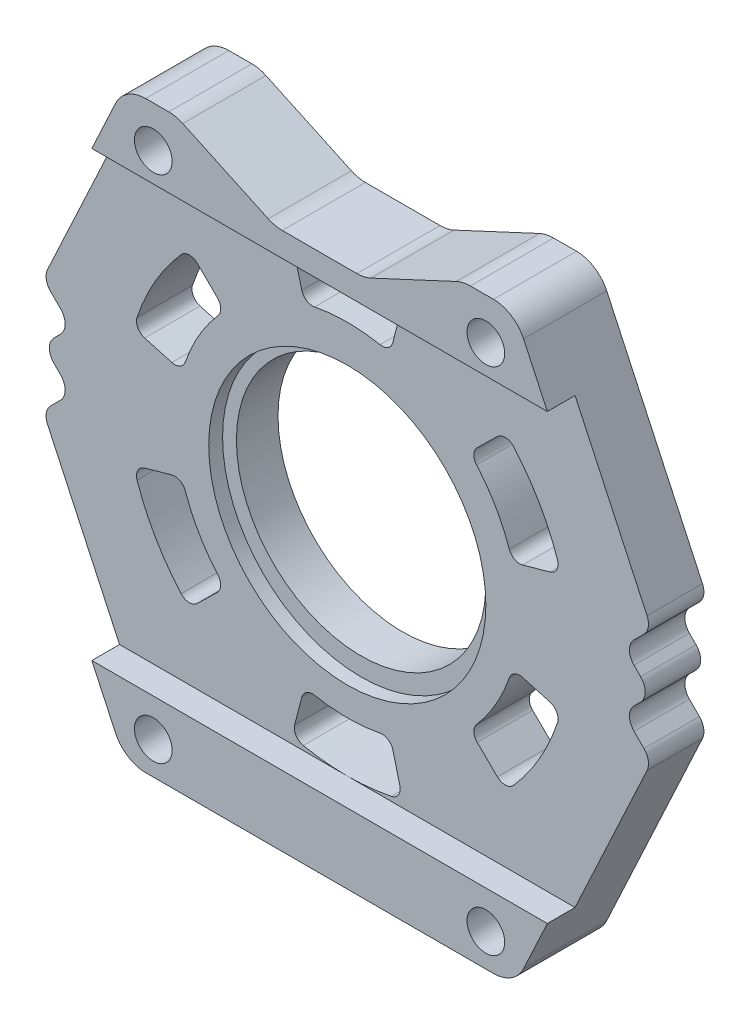
SolidWorks part; units mm, degrees
ref_plane "Front Plane" through (0, 0, 0) normal (0, 0, 1) x (1, 0, 0)
ref_plane "Top Plane" through (0, 0, 0) normal (0, 1, 0) x (1, 0, 0)
ref_plane "Right Plane" through (0, 0, 0) normal (1, 0, 0) x (0, 0, -1)
sketch "Sketch1" plane through (0, 0, 0) normal (0, 0, 1) x (1, 0, 0)
  line L1 (-34.8678, -33.4454) -> (34.8678, -33.4455)
  line L2 (-34.8678, -33.4454) -> (-34.8678, 33.4455)
  line L3 (-34.8678, 33.4455) -> (34.8678, 33.4455)
  line L4 (34.8678, -33.4455) -> (34.8678, 33.4455)
  line L5 (-34.8678, -33.4454) -> (34.8678, 33.4455) construction
  line L6 (-34.8678, 33.4455) -> (34.8678, -33.4455) construction
  circle A0 centre (0, 0) radius 14.2875
  point P0 (0, 0)
  dimension "D3" = 28.575
  dimension "D1" = 66.8909
  dimension "D2" = 69.7357
extrude "Boss-Extrude1" add sketch "Sketch1" along normal blind 9.525
sketch "Sketch2" plane through (0, 0, 9.525) normal (0, 0, 1) x (1, 0, 0)
  line L1 (-44.9984, -25.4) -> (44.9984, -25.4)
  line L2 (-44.9984, -25.4) -> (-44.9984, 25.4)
  line L3 (-44.9984, 25.4) -> (44.9984, 25.4)
  line L4 (44.9984, -25.4) -> (44.9984, 25.4)
  line L5 (-44.9984, -25.4) -> (44.9984, 25.4) construction
  line L6 (-44.9984, 25.4) -> (44.9984, -25.4) construction
  point P0 (0, 0)
  dimension "D1" = 50.8
extrude "Cut-Extrude1" cut sketch "Sketch2" against normal blind 3.175
sketch "Sketch3" plane through (0, 0, 6.35) normal (0, 0, 1) x (1, 0, 0)
  line L0 (-34.8678, -33.4454) -> (34.8678, -33.4455) construction
  line L1 (-34.8678, -33.4454) -> (34.8678, -33.4455) construction
  line L2 (0, -33.4455) -> (0, -16.3766) construction
  circle A0 centre (0, -0.5016) radius 15.875
  dimension "D1" = 31.75
  dimension "D2" = 17.0688
extrude "Cut-Extrude2" cut sketch "Sketch3" against normal blind 1.5875
sketch "Sketch4" plane through (0, 0, 0) normal (0, 0, -1) x (-1, 0, 0)
  line L0 (0, 0) -> (0, 33.4455) construction
  line L1 (-34.8678, 33.4455) -> (34.8678, 33.4455) construction
  line L2 (5.1189, 28.1763) -> (-5.1189, 28.1763)
  line L3 (-5.1189, 28.1763) -> (-16.436, 33.4455)
  line L4 (-16.436, 33.4455) -> (-22.3463, 33.4455)
  line L5 (-22.3463, 33.4455) -> (-34.8678, 6.5517)
  line L6 (-34.8678, -33.4455) -> (-34.8678, 33.4455) construction
  line L7 (-34.8678, 6.5517) -> (-31.592, 3.2758)
  line L8 (-31.592, 3.2758) -> (-34.8678, 0)
  line L9 (0, 0) -> (-34.8678, 0) construction
  line L11 (-48.1322, -47.2485) -> (-48.1322, 47.2485)
  line L13 (48.1322, 47.2485) -> (-48.1322, 47.2485)
  line L14 (48.1322, 0) -> (48.1322, 47.2485)
  line L16 (31.592, 3.2758) -> (34.8678, 0)
  line L17 (34.8678, 6.5517) -> (31.592, 3.2758)
  line L18 (22.3463, 33.4455) -> (34.8678, 6.5517)
  line L19 (16.436, 33.4455) -> (22.3463, 33.4455)
  line L20 (5.1189, 28.1763) -> (16.436, 33.4455)
  line L21 (48.1322, -47.2485) -> (48.1322, 47.2485)
  line L22 (16.436, -33.4455) -> (22.3463, -33.4455)
  line L23 (22.3463, -33.4455) -> (34.8678, -6.5517)
  line L24 (-31.592, -3.2758) -> (-34.8678, 0)
  line L25 (-34.8678, -6.5517) -> (-31.592, -3.2758)
  line L26 (-22.3463, -33.4455) -> (-34.8678, -6.5517)
  line L27 (-16.436, -33.4455) -> (-22.3463, -33.4455)
  line L28 (34.8678, -6.5517) -> (31.592, -3.2758)
  line L29 (31.592, -3.2758) -> (34.8678, 0)
  line L31 (31.592, 3.2758) -> (34.8678, 0)
  line L32 (-16.436, -33.4455) -> (16.436, -33.4455)
  line L33 (-48.1322, -47.2485) -> (48.1322, -47.2485)
  line M10 (-34.8678, 33.4455) -> (-34.8678, -33.4455)
  line M11 (-34.8678, -33.4455) -> (34.8678, -33.4454)
  line M12 (34.8678, -33.4454) -> (34.8678, 33.4455)
  line M13 (34.8678, 33.4455) -> (-34.8678, 33.4455)
extrude "Cut-Extrude3" cut sketch "Sketch4" against normal through all contours L5 M13 M10 | L8 L7 M10 | L25 L24 M10 | L26 M11 M10 | L23 M11 M12 | L2 L20 L3 M13 | L18 M13 M12 | L17 L16 M12 | L29 L28 M12
fillet "Fillet1" radius 3.81 8 edges at (-22.3463, 33.4455, 4.7625) (-22.3463, -33.4454, 4.7625) (22.3463, -33.4455, 4.7625) (-16.436, 33.4455, 4.7625) (-5.1189, 28.1763, 4.7625) (5.1189, 28.1763, 4.7625) (16.436, 33.4455, 4.7625) (22.3463, 33.4455, 4.7625)
fillet "Fillet2" radius 1.778 10 edges at (-34.8678, -6.5517, 3.175) (-31.592, -3.2758, 3.175) (-34.8679, 0, 3.175) (-31.592, 3.2758, 3.175) (-34.8679, 6.5517, 3.175) (34.8678, -6.5517, 3.175) (31.592, -3.2758, 3.175) (34.8679, 0, 3.175) (31.592, 3.2758, 3.175) (34.8679, 6.5517, 3.175)
sketch "Sketch5" plane through (0, 0, 0) normal (0, 0, -1) x (-1, 0, 0)
  line L0 (0, 0) -> (0, 25.4) construction
  line L1 (5.2148, 20.1969) -> (6.0241, 23.3314)
  line L2 (-5.2148, 20.1969) -> (-6.0241, 23.3314)
  line L3 (20.0984, 5.5823) -> (23.2176, 6.4486)
  line L4 (14.8836, 14.6146) -> (17.1935, 16.8828)
  line L5 (14.8836, -14.6146) -> (17.1935, -16.8828)
  line L6 (20.0984, -5.5823) -> (23.2176, -6.4486)
  line L7 (-5.2148, -20.1969) -> (-6.0241, -23.3314)
  line L8 (5.2148, -20.1969) -> (6.0241, -23.3314)
  line L9 (-20.0984, -5.5823) -> (-23.2176, -6.4486)
  line L10 (-14.8836, -14.6146) -> (-17.1935, -16.8828)
  line L11 (-14.8836, 14.6146) -> (-17.1935, 16.8828)
  line L12 (-20.0984, 5.5823) -> (-23.2176, 6.4486)
  arc A0 (3.743, 19.2677) -> (-3.743, 19.2677) centre (0, 0) ccw
  arc A1 (5.0468, 24.8936) -> (-5.0468, 24.8936) centre (0, 0) ccw
  arc A2 (0, 22.5751) -> (-5.6438, 21.8582) centre (0, 0) ccw construction
  arc A3 (0, 22.5751) -> (5.6438, 21.8582) centre (0, 0) cw construction
  arc A4 (3.743, 19.2677) -> (5.2148, 20.1969) centre (3.9851, 20.5144) ccw
  arc A5 (6.0241, 23.3314) -> (5.0468, 24.8936) centre (4.7945, 23.6489) ccw
  arc A6 (-6.0241, 23.3314) -> (-5.0468, 24.8936) centre (-4.7945, 23.6489) cw
  arc A7 (-3.743, 19.2677) -> (-5.2148, 20.1969) centre (-3.9851, 20.5144) cw
  arc A8 (18.5578, 6.3923) -> (14.8148, 12.8753) centre (0, 0) ccw
  arc A9 (24.0819, 8.0761) -> (19.0351, 16.8174) centre (0, 0) ccw
  arc A10 (18.5578, 6.3923) -> (20.0984, 5.5823) centre (19.7585, 6.806) ccw
  arc A11 (23.2176, 6.4486) -> (24.0819, 8.0761) centre (22.8778, 7.6723) ccw
  arc A12 (17.1935, 16.8828) -> (19.0351, 16.8174) centre (18.0833, 15.9766) cw
  arc A13 (14.8148, 12.8753) -> (14.8836, 14.6146) centre (15.7734, 13.7084) cw
  arc A14 (19.5506, 11.2875) -> (16.1079, 15.8168) centre (0, 0) ccw construction
  arc A15 (19.5506, 11.2875) -> (21.7517, 6.0415) centre (0, 0) cw construction
  arc A16 (14.8148, -12.8753) -> (18.5578, -6.3923) centre (0, 0) ccw
  arc A17 (19.0351, -16.8174) -> (24.0819, -8.0761) centre (0, 0) ccw
  arc A18 (14.8148, -12.8753) -> (14.8836, -14.6146) centre (15.7734, -13.7084) ccw
  arc A19 (17.1935, -16.8828) -> (19.0351, -16.8174) centre (18.0833, -15.9766) ccw
  arc A20 (23.2176, -6.4486) -> (24.0819, -8.0761) centre (22.8778, -7.6723) cw
  arc A21 (18.5578, -6.3923) -> (20.0984, -5.5823) centre (19.7585, -6.806) cw
  arc A22 (19.5506, -11.2875) -> (21.7517, -6.0415) centre (0, 0) ccw construction
  arc A23 (19.5506, -11.2875) -> (16.1079, -15.8168) centre (0, 0) cw construction
  arc A24 (-3.743, -19.2677) -> (3.743, -19.2677) centre (0, 0) ccw
  arc A25 (-5.0468, -24.8936) -> (5.0468, -24.8936) centre (0, 0) ccw
  arc A26 (-3.743, -19.2677) -> (-5.2148, -20.1969) centre (-3.9851, -20.5144) ccw
  arc A27 (-6.0241, -23.3314) -> (-5.0468, -24.8936) centre (-4.7945, -23.6489) ccw
  arc A28 (6.0241, -23.3314) -> (5.0468, -24.8936) centre (4.7945, -23.6489) cw
  arc A29 (3.743, -19.2677) -> (5.2148, -20.1969) centre (3.9851, -20.5144) cw
  arc A30 (0, -22.5751) -> (5.6438, -21.8582) centre (0, 0) ccw construction
  arc A31 (0, -22.5751) -> (-5.6438, -21.8582) centre (0, 0) cw construction
  arc A32 (-18.5578, -6.3923) -> (-14.8148, -12.8753) centre (0, 0) ccw
  arc A33 (-24.0819, -8.0761) -> (-19.0351, -16.8174) centre (0, 0) ccw
  arc A34 (-18.5578, -6.3923) -> (-20.0984, -5.5823) centre (-19.7585, -6.806) ccw
  arc A35 (-23.2176, -6.4486) -> (-24.0819, -8.0761) centre (-22.8778, -7.6723) ccw
  arc A36 (-17.1935, -16.8828) -> (-19.0351, -16.8174) centre (-18.0833, -15.9766) cw
  arc A37 (-14.8148, -12.8753) -> (-14.8836, -14.6146) centre (-15.7734, -13.7084) cw
  arc A38 (-19.5506, -11.2875) -> (-16.1079, -15.8168) centre (0, 0) ccw construction
  arc A39 (-19.5506, -11.2875) -> (-21.7517, -6.0415) centre (0, 0) cw construction
  arc A40 (-14.8148, 12.8753) -> (-18.5578, 6.3923) centre (0, 0) ccw
  arc A41 (-19.0351, 16.8174) -> (-24.0819, 8.0761) centre (0, 0) ccw
  arc A42 (-14.8148, 12.8753) -> (-14.8836, 14.6146) centre (-15.7734, 13.7084) ccw
  arc A43 (-17.1935, 16.8828) -> (-19.0351, 16.8174) centre (-18.0833, 15.9766) ccw
  arc A44 (-23.2176, 6.4486) -> (-24.0819, 8.0761) centre (-22.8778, 7.6723) cw
  arc A45 (-18.5578, 6.3923) -> (-20.0984, 5.5823) centre (-19.7585, 6.806) cw
  arc A46 (-19.5506, 11.2875) -> (-21.7517, 6.0415) centre (0, 0) ccw construction
  arc A47 (-19.5506, 11.2875) -> (-16.1079, 15.8168) centre (0, 0) cw construction
  point P14 (6.35, 24.5934)
  point P17 (-6.35, 24.5934)
  point P98 (0, 0)
  dimension "D1" = 39.2557
  dimension "D2" = 50.8
  dimension "D3" = 12.7
  dimension "D4" = 1.27
extrude "Cut-Extrude4" cut sketch "Sketch5" against normal through all
sketch "Sketch6" plane through (0, 0, 9.525) normal (0, 0, 1) x (1, 0, 0)
  line L1 (-19.05, -29.7116) -> (19.05, -29.7116) construction
  line L2 (-19.05, -29.7116) -> (-19.05, 28.7083) construction
  line L3 (-19.05, 28.7083) -> (19.05, 28.7084) construction
  line L4 (19.05, -29.7116) -> (19.05, 28.7084) construction
  line L5 (-19.05, -29.7116) -> (19.05, 28.7084) construction
  line L6 (-19.05, 28.7083) -> (19.05, -29.7116) construction
  circle A0 centre (-19.05, 28.7083) radius 2.159
  circle A1 centre (19.05, 28.7084) radius 2.159
  circle A2 centre (-19.05, -29.7116) radius 2.159
  circle A3 centre (19.05, -29.7116) radius 2.159
  point P0 (0, -0.5016)
  dimension "D3" = 4.318
  dimension "D1" = 58.42
  dimension "D2" = 38.1
extrude "Cut-Extrude5" cut sketch "Sketch6" against normal through all
